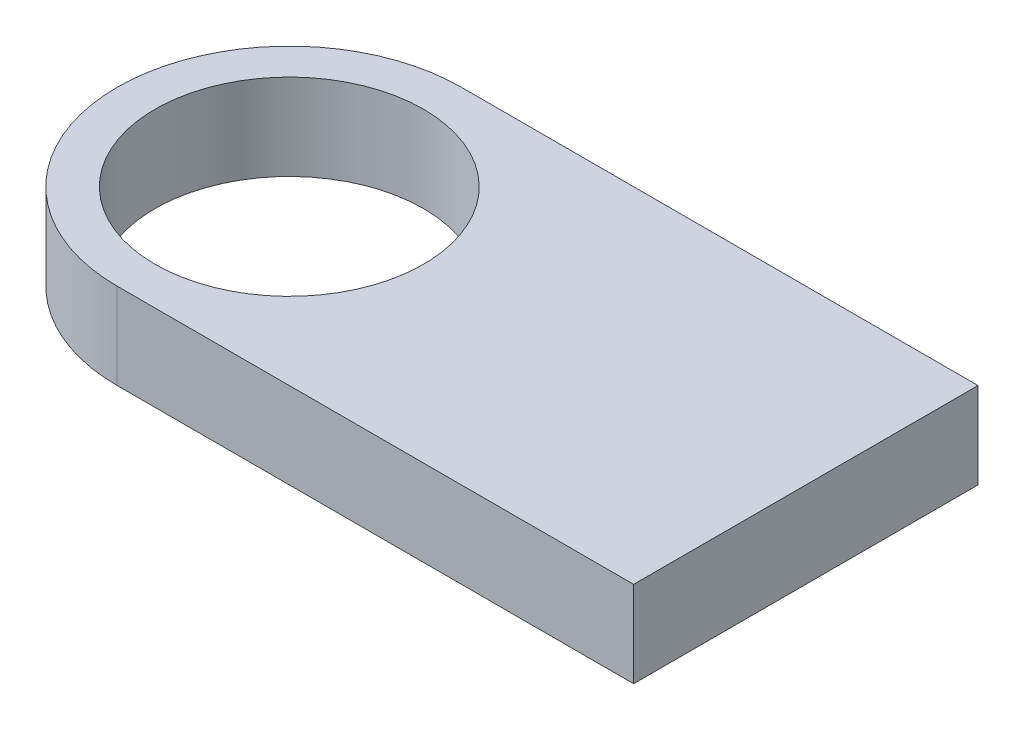
SolidWorks part; units mm, degrees
ref_plane "Alzado" through (0, 0, 0) normal (0, 0, 1) x (1, 0, 0)
ref_plane "Planta" through (0, 0, 0) normal (0, 1, 0) x (1, 0, 0)
ref_plane "Vista lateral" through (0, 0, 0) normal (1, 0, 0) x (0, 0, -1)
sketch "Croquis1" plane through (0, 0, 0) normal (0, 1, 0) x (1, 0, 0)
  line L1 (0, -10) -> (30, -10)
  line L3 (0, 10) -> (30, 10)
  line L4 (30, -10) -> (30, 10)
  arc A1 (0, 10) -> (0, -10) centre (0, 0) ccw
  dimension "D2" = 20
  dimension "D3" = 20
  dimension "D4" = 30
extrude "Saliente-Extruir1" add sketch "Croquis1" along normal blind 5 contours A1 L1 L4 L3
sketch "Croquis2" plane through (0, 5, 0) normal (0, 1, 0) x (1, 0, 0)
  circle A0 centre (0, 0) radius 7.8
  dimension "D1" = 15.6
extrude "Cortar-Extruir1" cut sketch "Croquis2" against normal blind 5
